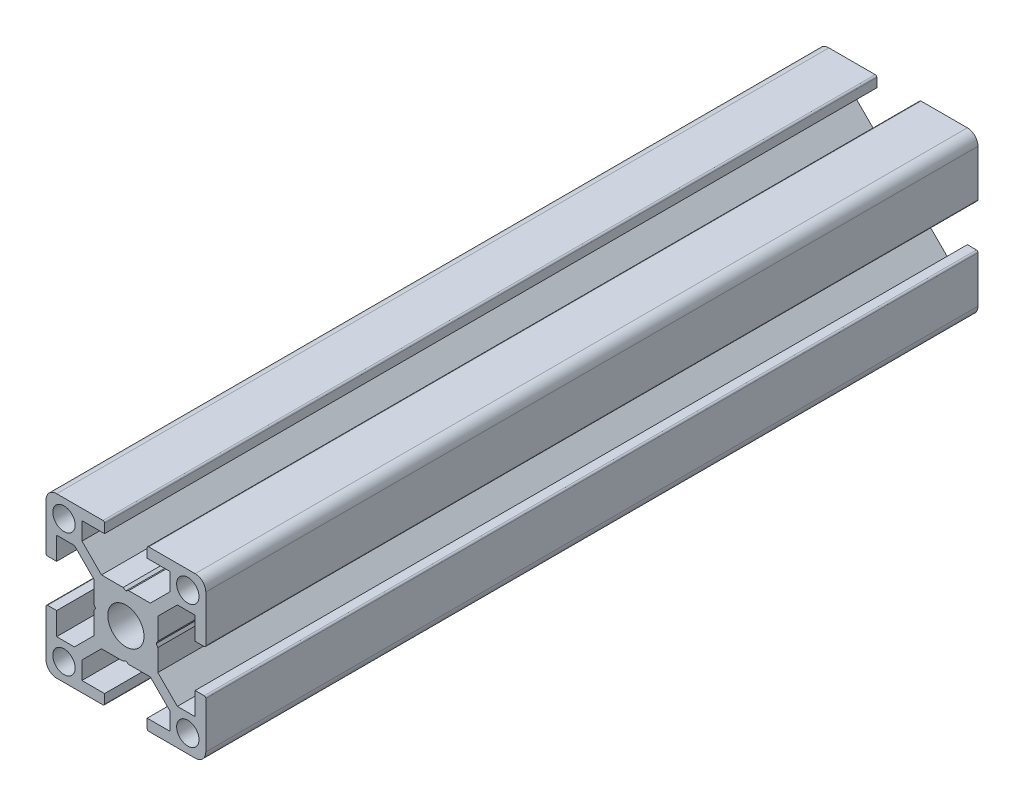
SolidWorks part; units mm, degrees
ref_plane "Front Plane" through (0, 0, 0) normal (0, 0, 1) x (1, 0, 0)
ref_plane "Top Plane" through (0, 0, 0) normal (0, 1, 0) x (1, 0, 0)
ref_plane "Right Plane" through (0, 0, 0) normal (1, 0, 0) x (0, 0, -1)
sketch "Sketch1" plane through (0, 0, 0) normal (0, 0, 1) x (1, 0, 0)
  line L0 (-14.7, 4) -> (-13, 4)
  line L1 (-13, 4) -> (-13, 8.25)
  line L2 (-13, 8.25) -> (-9.6642, 8.25)
  line L3 (-9.6642, 8.25) -> (-6, 4.5858)
  line L4 (-6, 4.5858) -> (-6, 0.5196)
  line L5 (-6, 0.5196) -> (-5.7, 0)
  line L6 (-5.7, 0) -> (-6, -0.5196)
  line L7 (-6, -0.5196) -> (-6, -4.5858)
  line L8 (-6, -4.5858) -> (-9.6642, -8.25)
  line L9 (-9.6642, -8.25) -> (-13, -8.25)
  line L10 (-13, -8.25) -> (-13, -4)
  line L11 (-13, -4) -> (-14.7, -4)
  line L12 (-15, -4.3) -> (-15, -13)
  line L13 (-13, -15) -> (-4.3, -15)
  line L14 (-4, -14.7) -> (-4, -13)
  line L15 (-4, -13) -> (-8.25, -13)
  line L16 (-8.25, -13) -> (-8.25, -9.6642)
  line L17 (-8.25, -9.6642) -> (-4.5858, -6)
  line L18 (-4.5858, -6) -> (-0.5196, -6)
  line L19 (-0.5196, -6) -> (0, -5.7)
  line L20 (0, -5.7) -> (0.5196, -6)
  line L21 (0.5196, -6) -> (4.5858, -6)
  line L22 (4.5858, -6) -> (8.25, -9.6642)
  line L23 (8.25, -9.6642) -> (8.25, -13)
  line L24 (8.25, -13) -> (4, -13)
  line L25 (4, -13) -> (4, -14.7)
  line L26 (4.3, -15) -> (13, -15)
  line L27 (15, -13) -> (15, -4.3)
  line L28 (14.7, -4) -> (13, -4)
  line L29 (13, -4) -> (13, -8.25)
  line L30 (13, -8.25) -> (9.6642, -8.25)
  line L31 (9.6642, -8.25) -> (6, -4.5858)
  line L32 (6, -4.5858) -> (6, -0.5196)
  line L33 (6, -0.5196) -> (5.7, 0)
  line L34 (5.7, 0) -> (6, 0.5196)
  line L35 (6, 0.5196) -> (6, 4.5858)
  line L36 (6, 4.5858) -> (9.6642, 8.25)
  line L37 (9.6642, 8.25) -> (13, 8.25)
  line L38 (13, 8.25) -> (13, 4)
  line L39 (13, 4) -> (14.7, 4)
  line L40 (15, 4.3) -> (15, 13)
  line L41 (13, 15) -> (4.3, 15)
  line L42 (4, 14.7) -> (4, 13)
  line L43 (4, 13) -> (8.25, 13)
  line L44 (8.25, 13) -> (8.25, 9.6642)
  line L45 (8.25, 9.6642) -> (4.5858, 6)
  line L46 (4.5858, 6) -> (0.5196, 6)
  line L47 (0.5196, 6) -> (0, 5.7)
  line L48 (0, 5.7) -> (-0.5196, 6)
  line L49 (-0.5196, 6) -> (-4.5858, 6)
  line L50 (-4.5858, 6) -> (-8.25, 9.6642)
  line L51 (-8.25, 9.6642) -> (-8.25, 13)
  line L52 (-8.25, 13) -> (-4, 13)
  line L53 (-4, 13) -> (-4, 14.7)
  line L54 (-4.3, 15) -> (-13, 15)
  line L55 (-15, 13) -> (-15, 4.3)
  arc A0 (-15, 4.3) -> (-14.7, 4) centre (-14.7, 4.3) ccw
  arc A1 (-14.7, -4) -> (-15, -4.3) centre (-14.7, -4.3) ccw
  arc A2 (-15, -13) -> (-13, -15) centre (-13, -13) ccw
  arc A3 (-4.3, -15) -> (-4, -14.7) centre (-4.3, -14.7) ccw
  arc A4 (4, -14.7) -> (4.3, -15) centre (4.3, -14.7) ccw
  arc A5 (13, -15) -> (15, -13) centre (13, -13) ccw
  arc A6 (15, -4.3) -> (14.7, -4) centre (14.7, -4.3) ccw
  arc A7 (14.7, 4) -> (15, 4.3) centre (14.7, 4.3) ccw
  arc A8 (15, 13) -> (13, 15) centre (13, 13) ccw
  arc A9 (4.3, 15) -> (4, 14.7) centre (4.3, 14.7) ccw
  arc A10 (-4, 14.7) -> (-4.3, 15) centre (-4.3, 14.7) ccw
  arc A11 (-13, 15) -> (-15, 13) centre (-13, 13) ccw
  circle A12 centre (11.625, 11.625) radius 2.1
  circle A13 centre (11.625, -11.625) radius 2.1
  circle A14 centre (0, 0) radius 3.4
  circle A15 centre (-11.625, -11.625) radius 2.1
  circle A16 centre (-11.625, 11.625) radius 2.1
extrude "Boss-Extrude1" add sketch "Sketch1" along normal blind 145
